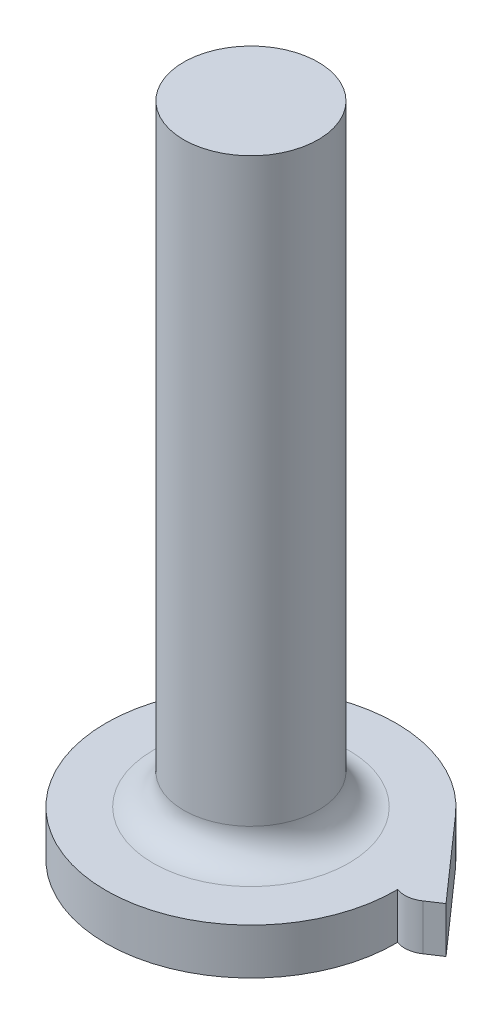
SolidWorks part; units mm, degrees
ref_plane "Alzado" through (0, 0, 0) normal (0, 0, 1) x (1, 0, 0)
ref_plane "Planta" through (0, 0, 0) normal (0, 1, 0) x (1, 0, 0)
ref_plane "Vista lateral" through (0, 0, 0) normal (1, 0, 0) x (0, 0, -1)
sketch "Croquis1" plane through (0, 0, 0) normal (0, 1, 0) x (1, 0, 0)
  line L0 (-28.2858, 109.1591) -> (-30.6661, 111.8526) construction
  line L1 (-28.2858, 109.1591) -> (-30.6661, 111.8526)
  line L2 (-28.7436, 108.8563) -> (-28.2858, 109.1591) construction
  line L3 (-28.7436, 108.8563) -> (-28.2858, 109.1591)
  arc A1 (-30.6661, 111.8526) -> (-34.2208, 113.4551) centre (-34.2208, 108.7112) ccw construction
  arc A2 (-30.6661, 111.8526) -> (-34.2208, 113.4551) centre (-34.2208, 108.7112) ccw
  arc A3 (-30.6661, 111.8526) -> (-29.4772, 108.7687) centre (-34.2208, 108.7112) ccw
  arc A4 (-29.794, 108.9873) -> (-28.7436, 108.8563) centre (-29.1946, 109.5171) ccw construction
  arc A5 (-29.4772, 108.7687) -> (-28.7436, 108.8563) centre (-29.1946, 109.5171) ccw
extrude "Saliente-Extruir1" add sketch "Croquis1" along normal blind 1.5 contours A3 A5 L3 L1 A2
sketch "Croquis2" plane through (0, 1.5, 0) normal (0, 1, 0) x (1, 0, 0)
  circle A3 centre (-34.2208, 108.7112) radius 2.2
  dimension "D1" = 4.4
extrude "Saliente-Extruir2" add sketch "Croquis2" along normal blind 20
fillet "Fillet2" radius 1 1 edges at (-34.2208, 1.5, -106.5112)
sketch "Sketch1" plane through (0, 0, 0) normal (0, -1, 0) x (1, 0, 0)
  circle A0 centre (-34.2208, -108.7112) radius 2.5
  arc A1 (-29.4772, -108.7687) -> (-30.6661, -111.8526) centre (-34.2208, -108.7112) ccw construction
  point P2 (0, 0)
  dimension "D1" = 5
extrude "Cut-Extrude1" cut sketch "Sketch1" against normal blind 0.5
